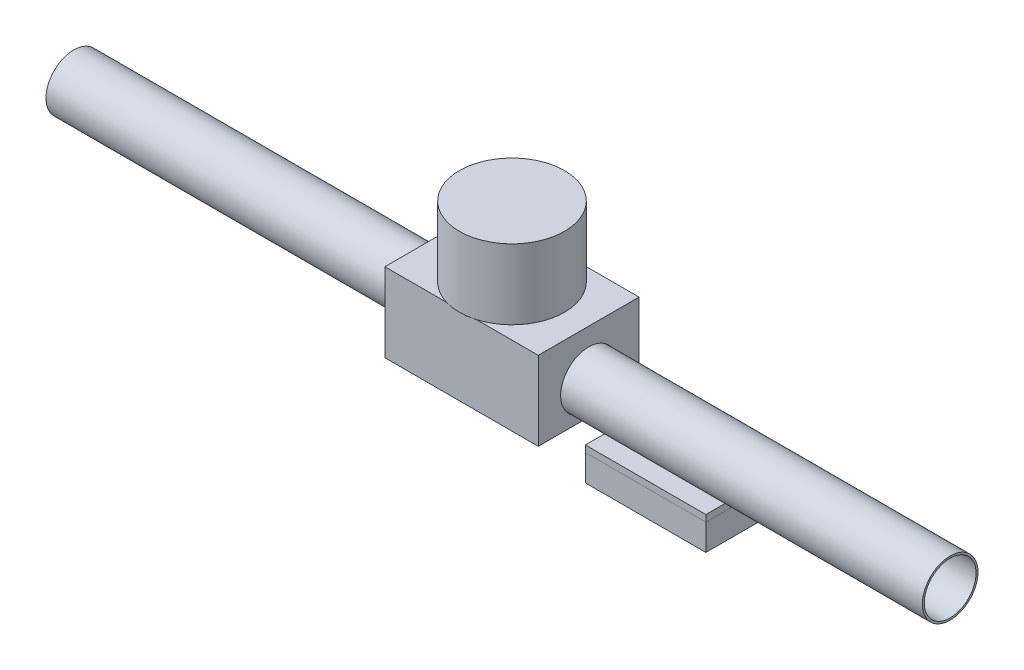
SolidWorks part; units mm, degrees
ref_plane "Front Plane" through (0, 0, 0) normal (0, 0, 1) x (1, 0, 0)
ref_plane "Top Plane" through (0, 0, 0) normal (0, 1, 0) x (1, 0, 0)
ref_plane "Right Plane" through (0, 0, 0) normal (1, 0, 0) x (0, 0, -1)
sketch "Sketch1" plane through (0, 0, 0) normal (1, 0, 0) x (0, 0, -1)
  circle A0 centre (0, 0) radius 12.7
  circle A1 centre (0, 0) radius 11.811
extrude "Boom" add sketch "Sketch1" along normal mid plane 400 separate body
sketch "Sketch2" plane through (0, 0, 0) normal (1, 0, 0) x (0, 0, -1)
  line L1 (-23, -15) -> (23, -15)
  line L2 (-23, -15) -> (-23, 21)
  line L3 (-23, 21) -> (23, 21)
  line L4 (23, -15) -> (23, 21)
  circle A0 centre (0, 0) radius 12.8
extrude "Mount" add sketch "Sketch2" along normal mid plane 70 separate body
sketch "Sketch3" plane through (0, 0, 0) normal (0, 1, 0) x (1, 0, 0)
  circle A0 centre (0, 0) radius 24
extrude "Motor" add sketch "Sketch3" along normal blind 32 from offset 21 separate body
sketch "Sketch4" plane through (0, 0, 0) normal (0, 1, 0) x (1, 0, 0)
  line L1 (47.5, -14) -> (102.5, -14)
  line L2 (47.5, -14) -> (47.5, 14)
  line L3 (47.5, 14) -> (102.5, 14)
  line L4 (102.5, -14) -> (102.5, 14)
extrude "Pad" add sketch "Sketch4" against normal blind 3 from offset 12.7 separate body
sketch "Sketch5" plane through (0, 0, 0) normal (0, 1, 0) x (1, 0, 0)
  line L1 (47.5, -14) -> (102.5, -14)
  line L2 (47.5, -14) -> (47.5, 14)
  line L3 (47.5, 14) -> (102.5, 14)
  line L4 (102.5, -14) -> (102.5, 14)
extrude "ESC" add sketch "Sketch5" against normal blind 12 from offset 15.7 separate body
